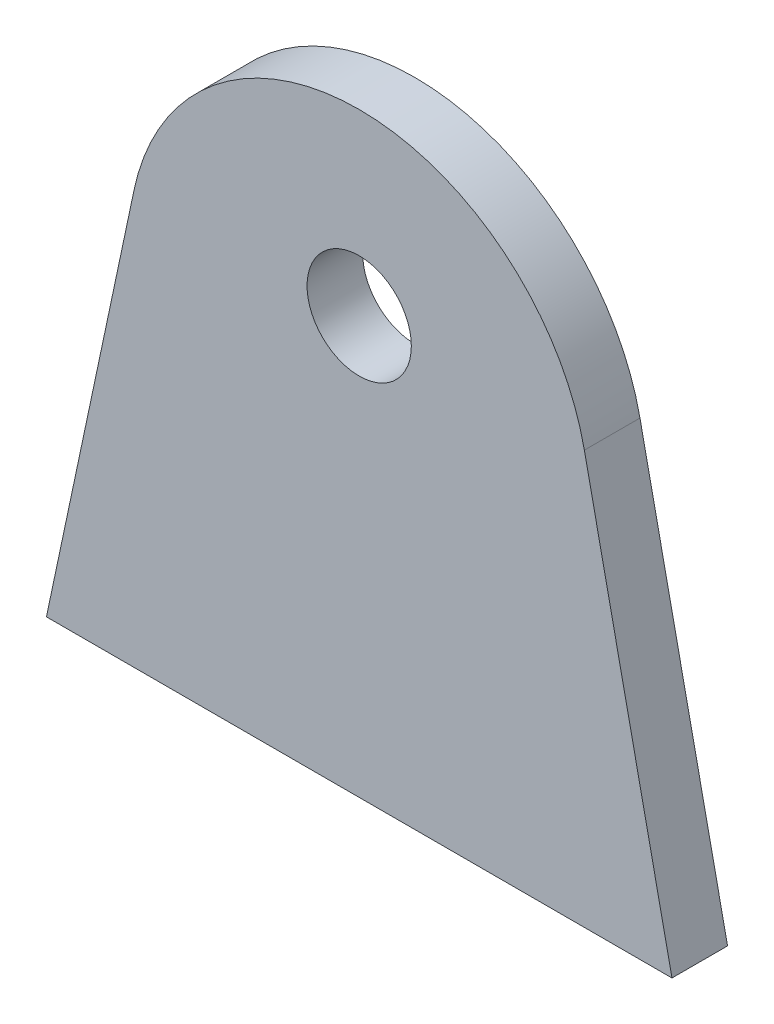
SolidWorks part; units mm, degrees
ref_plane "Front Plane" through (0, 0, 0) normal (0, 0, 1) x (1, 0, 0)
ref_plane "Top Plane" through (0, 0, 0) normal (0, 1, 0) x (1, 0, 0)
ref_plane "Right Plane" through (0, 0, 0) normal (1, 0, 0) x (0, 0, -1)
sketch "Sketch1" plane through (0, 0, 0) normal (0, 0, 1) x (1, 0, 0)
  line L0 (0, 0) -> (28.575, 0)
  line L5 (0, 0) -> (4.0018, 18.8818)
  line L6 (24.5732, 18.8818) -> (28.575, 0)
  circle A0 centre (14.2875, 19.05) radius 2.3813
  arc A1 (4.0018, 18.8818) -> (24.5732, 18.8818) centre (14.2875, 16.7019) cw
  point P5 (14.2875, 0)
  point P8 (0, 0)
  point P10 (14.2875, 27.2161)
  point P11 (0, 0)
  dimension "D3" = 4.7625
  dimension "D1" = 28.575
  dimension "D2" = 8.1661
  dimension "D4" = 19.05
  dimension "D5" = 27.2161
extrude "Boss-Extrude1" add sketch "Sketch1" against normal blind 2.54
